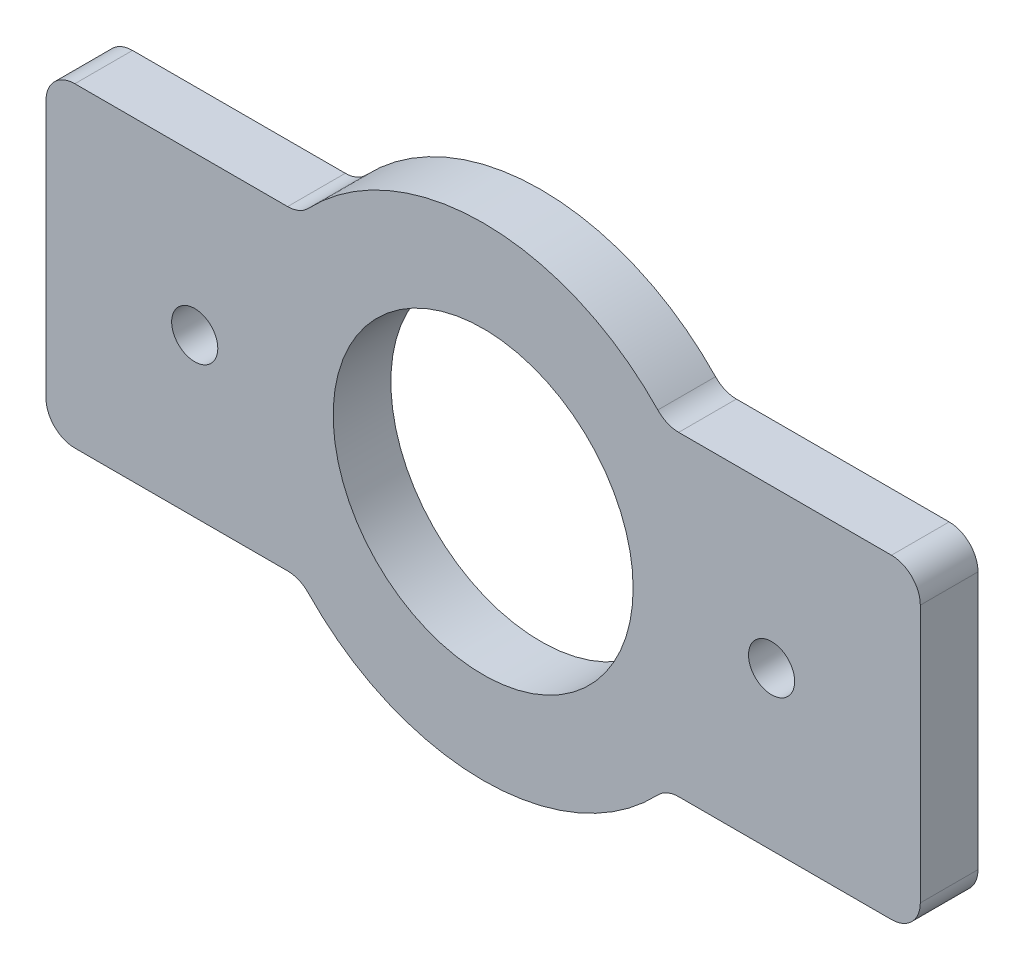
SolidWorks part; units mm, degrees
material "1023 Carbon Steel Sheet (SS)"
ref_plane "Front Plane" through (0, 0, 0) normal (0, 0, 1) x (1, 0, 0)
ref_plane "Top Plane" through (0, 0, 0) normal (0, 1, 0) x (1, 0, 0)
ref_plane "Right Plane" through (0, 0, 0) normal (1, 0, 0) x (0, 0, -1)
sketch "Sketch1" plane through (0, 0, 0) normal (0, 0, 1) x (1, 0, 0)
  line L5 (31.6848, 27.352) -> (75.7826, 27.352)
  line L6 (31.6848, -27.352) -> (75.7826, -27.352)
  line L8 (-75.7826, 27.352) -> (-31.6848, 27.352)
  line L13 (-75.7826, -27.352) -> (-31.6848, -27.352)
  line L14 (-75.7826, -27.352) -> (-75.7826, 27.352)
  line L16 (75.7826, -27.352) -> (75.7826, 27.352)
  circle A0 centre (0, 0) radius 26
  arc A4 (-31.6848, -27.352) -> (31.6848, -27.352) centre (0, 0) ccw
  arc A5 (31.6848, 27.352) -> (-31.6848, 27.352) centre (0, 0) ccw
  point P0 (0, 0)
  dimension "D1" = 52
extrude "Boss-Extrude1" add sketch "Sketch1" along normal blind 10
fillet "Fillet1" radius 5 8 edges at (75.7826, -27.352, 5) (31.6848, -27.352, 5) (-31.6848, -27.352, 5) (-75.7826, -27.352, 5) (-75.7826, 27.352, 5) (75.7826, 27.352, 5) (31.6848, 27.352, 5) (-31.6848, 27.352, 5)
sketch "Sketch2" plane through (0, 0, 10) normal (0, 0, 1) x (1, 0, 0)
  line L0 (0, -5.5) -> (0, 5.5) construction
  line L1 (-67.9849, 0) -> (61.6607, 0) construction
  circle A0 centre (-50, 0) radius 4
  circle A1 centre (50, 0) radius 4
  dimension "D1" = 8
  dimension "D2" = 8
  dimension "D3" = 50
  dimension "D4" = 50
extrude "Cut-Extrude1" cut sketch "Sketch2" against normal blind 10
